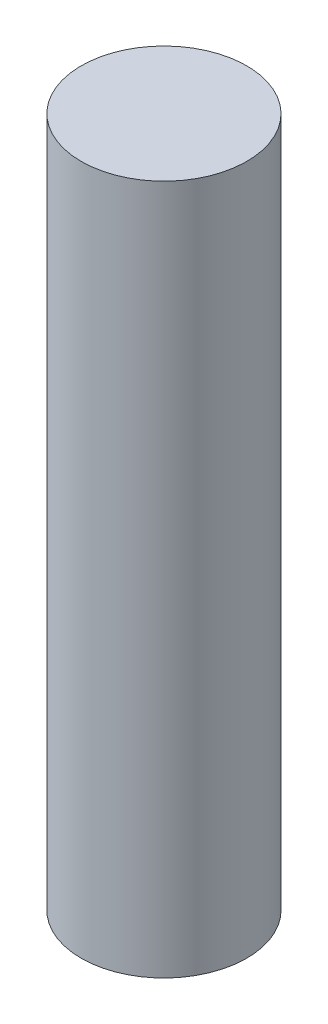
SolidWorks part; units mm, degrees
ref_plane "Front Plane" through (0, 0, 0) normal (0, 0, 1) x (1, 0, 0)
ref_plane "Top Plane" through (0, 0, 0) normal (0, 1, 0) x (1, 0, 0)
ref_plane "Right Plane" through (0, 0, 0) normal (1, 0, 0) x (0, 0, -1)
sketch "Sketch1" plane through (0, 0, 0) normal (0, 1, 0) x (1, 0, 0)
  circle A0 centre (0, 0) radius 12
  dimension "D1" = 24
extrude "Boss-Extrude1" add sketch "Sketch1" along normal blind 100
